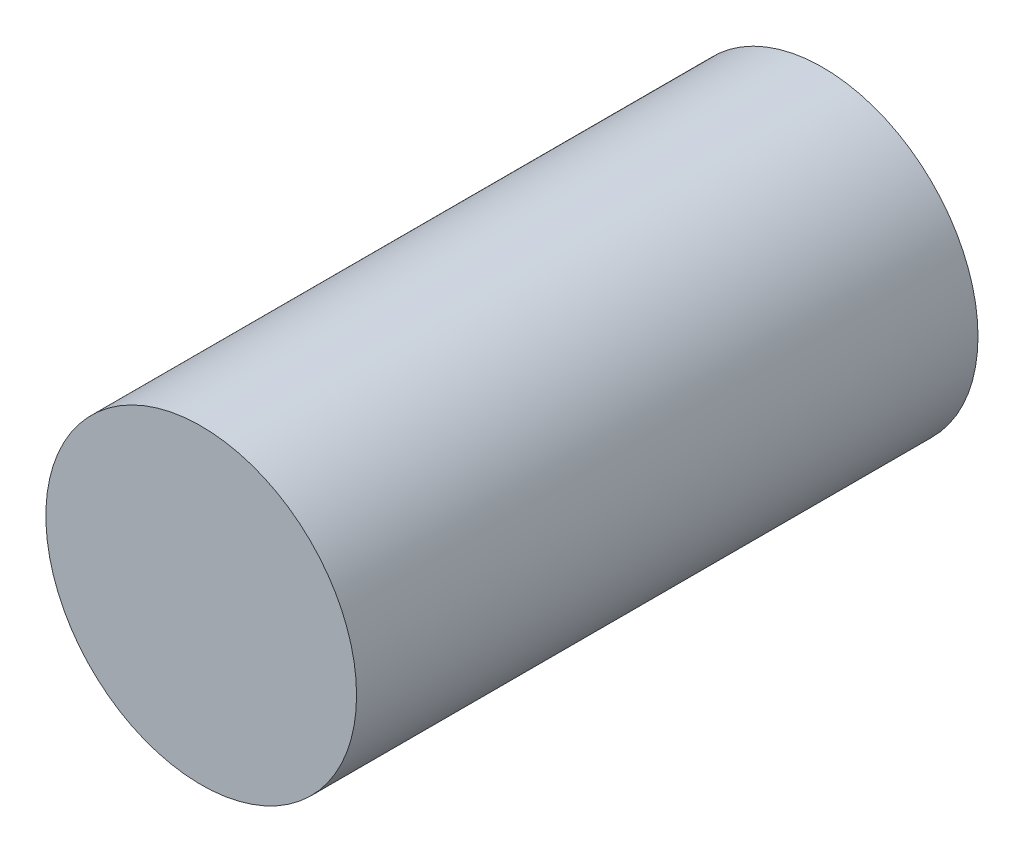
SolidWorks part; units mm, degrees
ref_plane "Front" through (0, 0, 0) normal (0, 0, 1) x (1, 0, 0)
ref_plane "Top" through (0, 0, 0) normal (0, 1, 0) x (1, 0, 0)
ref_plane "Right" through (0, 0, 0) normal (1, 0, 0) x (0, 0, -1)
sketch "Esquisse1" plane through (0, 0, 0) normal (0, 0, 1) x (1, 0, 0)
  circle A0 centre (0, 0) radius 27.5
  dimension "D1" = 55
extrude "Boss.-Extru.1" add sketch "Esquisse1" along normal mid plane 110
